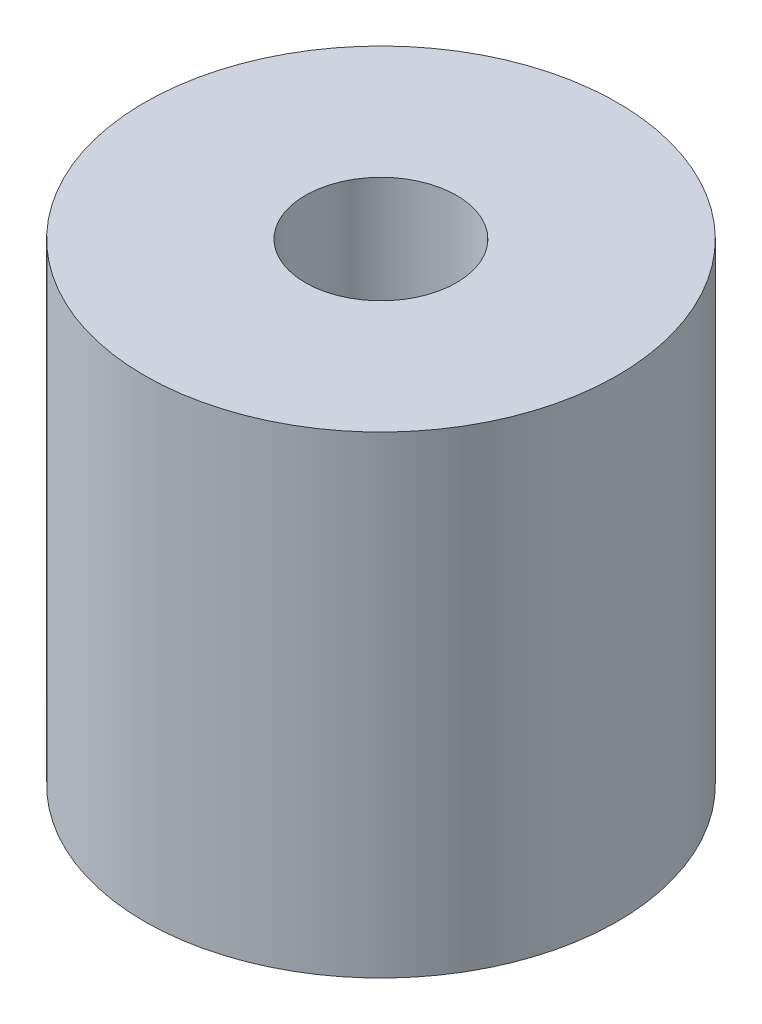
SolidWorks part; units mm, degrees
ref_plane "Alzado" through (0, 0, 0) normal (0, 0, 1) x (1, 0, 0)
ref_plane "Planta" through (0, 0, 0) normal (0, 1, 0) x (1, 0, 0)
ref_plane "Vista lateral" through (0, 0, 0) normal (1, 0, 0) x (0, 0, -1)
sketch "Croquis1" plane through (0, 0, 0) normal (0, 1, 0) x (1, 0, 0)
  circle A0 centre (0, 0) radius 12.5
  dimension "D1" = 25
extrude "Saliente-Extruir1" add sketch "Croquis1" along normal blind 25
sketch "Croquis2" plane through (0, 25, 0) normal (0, 1, 0) x (1, 0, 0)
  circle A0 centre (0, 0) radius 4
  dimension "D1" = 8
extrude "Cortar-Extruir1" cut sketch "Croquis2" against normal blind 15
sketch "Croquis3" plane through (0, 0, 0) normal (0, -1, 0) x (1, 0, 0)
  circle A0 centre (0, 0) radius 3.175
  dimension "D1" = 6.35
extrude "Cortar-Extruir2" cut sketch "Croquis3" against normal blind 15
